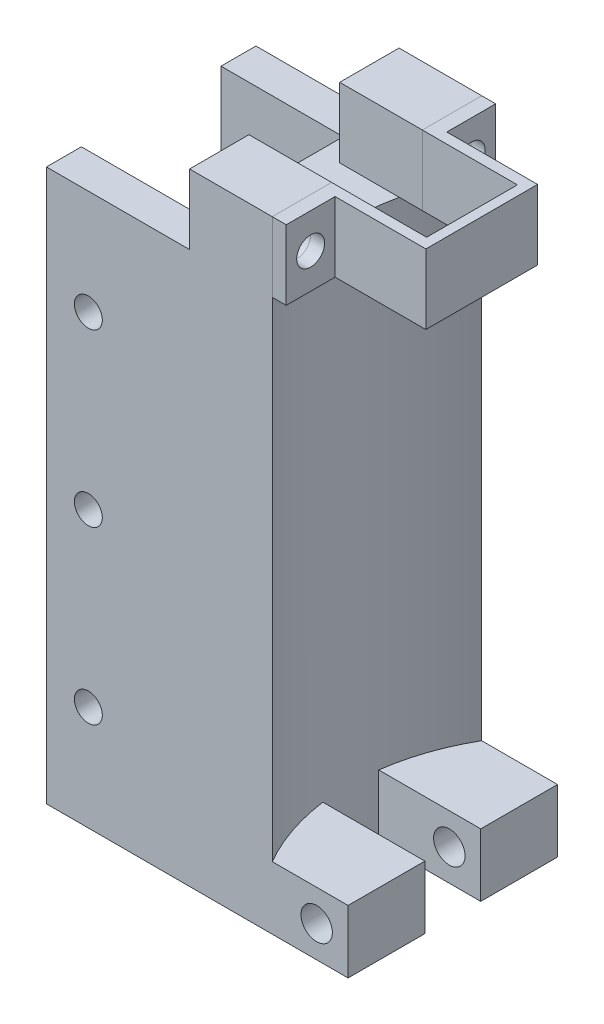
SolidWorks part; units mm, degrees
ref_plane "Front Plane" through (0, 0, 0) normal (0, 0, 1) x (1, 0, 0)
ref_plane "Top Plane" through (0, 0, 0) normal (0, 1, 0) x (1, 0, 0)
ref_plane "Right Plane" through (0, 0, 0) normal (1, 0, 0) x (0, 0, -1)
sketch "Sketch1" plane through (0, 0, 0) normal (0, 0, 1) x (1, 0, 0)
  line L1 (-7.5, -39.5) -> (7.5, -39.5)
  line L2 (-7.5, -39.5) -> (-7.5, 39.5)
  line L3 (-7.5, 39.5) -> (7.5, 39.5)
  line L4 (7.5, -39.5) -> (7.5, 39.5)
  line L5 (-7.5, -39.5) -> (7.5, 39.5) construction
  line L6 (-7.5, 39.5) -> (7.5, -39.5) construction
  point P0 (0, 0)
  dimension "D1" = 15
  dimension "D2" = 79
extrude "Boss-Extrude1" add sketch "Sketch1" along normal mid plane 30
sketch "Sketch2" plane through (0, 39.5, 0) normal (0, 1, 0) x (1, 0, 0)
  arc A0 (7.5, -15) -> (7.5, 15) centre (33.4808, 0) cw
  line M5 (7.5, -15) -> (7.5, 15)
  dimension "D1" = 30
extrude "Cut-Extrude1" cut sketch "Sketch2" against normal blind 70 and the other way through all contours A0 M5
sketch "Sketch3" plane through (7.5, 0, 0) normal (1, 0, 0) x (0, 0, -1)
  line L4 (15, -30.5) -> (-15, -30.5)
  line L5 (-15, -30.5) -> (-15, -39.5)
  line L6 (-15, -39.5) -> (15, -39.5)
  line L7 (15, -39.5) -> (15, -30.5)
  line L8 (15, -30.5) -> (-15, -30.5)
  line L9 (-15, -30.5) -> (-15, -39.5)
  line L10 (-15, -39.5) -> (15, -39.5)
  line L11 (15, -39.5) -> (15, -30.5)
  dimension "D1" = 0
extrude "Boss-Extrude2" add sketch "Sketch3" along normal blind 10.86
sketch "Sketch4" plane through (0, 0, -15) normal (0, 0, -1) x (-1, 0, 0)
  line L6 (-7.5, 39.5) -> (-7.5, -30.5)
  line L7 (-7.5, -30.5) -> (-18.36, -30.5)
  line L8 (-18.36, -30.5) -> (-18.36, -39.5)
  line L9 (-18.36, -39.5) -> (7.5, -39.5)
  line L10 (7.5, -39.5) -> (7.5, 39.5)
  line L11 (7.5, 39.5) -> (-7.5, 39.5)
  line L12 (-7.5, 39.5) -> (-7.5, -30.5)
  line L13 (-7.5, -30.5) -> (-18.36, -30.5)
  line L14 (-18.36, -30.5) -> (-18.36, -39.5)
  line L15 (-18.36, -39.5) -> (7.5, -39.5)
  line L16 (7.5, -39.5) -> (7.5, 39.5)
  line L17 (7.5, 39.5) -> (-7.5, 39.5)
  circle A0 centre (-13.86, -35) radius 2.25
  dimension "D2" = 4.5
  dimension "D4" = 4.5
  dimension "D3" = 4.5
  dimension "D1" = 0
extrude "Cut-Extrude2" cut sketch "Sketch4" against normal blind 50.86 contours A0
sketch "Sketch5" plane through (18.36, 0, 0) normal (1, 0, 0) x (0, 0, -1)
  line L0 (-15, -39.5) -> (15, -39.5) construction
  line L1 (-4, -39.5) -> (4, -39.5)
  line L2 (-4, -39.5) -> (-4, -30.5)
  line L3 (-4, -30.5) -> (4, -30.5)
  line L4 (4, -39.5) -> (4, -30.5)
  line L5 (15, -30.5) -> (-15, -30.5) construction
  line L6 (-15, -30.5) -> (-15, -39.5) construction
  line M6 (15, -30.5) -> (-15, -30.5)
  line M8 (-15, -39.5) -> (15, -39.5)
  dimension "D1" = 8
  dimension "D2" = 11
extrude "Cut-Extrude3" cut sketch "Sketch5" against normal up to surface (14.6114 mm away) contours L4 L2 M8 M6
sketch "Sketch8" plane through (0, 0, 0) normal (0, 0, 1) x (1, 0, 0)
  line L1 (0, -39.5) -> (-24.84, -39.5)
  line L2 (0, -39.5) -> (0, 39.5)
  line L3 (0, 39.5) -> (-24.84, 39.5)
  line L4 (-24.84, -39.5) -> (-24.84, 39.5)
  line L6 (-7.5, -39.5) -> (18.36, -39.5)
  line L7 (18.36, -39.5) -> (18.36, -30.5)
  line L8 (18.36, -30.5) -> (7.5, -30.5)
  line L9 (7.5, -30.5) -> (7.5, 39.5)
  line L10 (7.5, 39.5) -> (-7.5, 39.5)
  line L11 (-7.5, 39.5) -> (-7.5, -39.5)
  line L12 (-7.5, -39.5) -> (18.36, -39.5)
  line L13 (18.36, -39.5) -> (18.36, -30.5)
  line L14 (18.36, -30.5) -> (7.5, -30.5)
  line L15 (7.5, -30.5) -> (7.5, 39.5)
  line L16 (7.5, 39.5) -> (-7.5, 39.5)
  line L17 (-7.5, 39.5) -> (-7.5, -39.5)
  dimension "D2" = 24.84
  dimension "D1" = 0
extrude "Boss-Extrude3" add sketch "Sketch8" along normal mid plane 30 contours L17 L3 L4 L1
sketch "Sketch9" plane through (-24.84, 0, 0) normal (-1, 0, 0) x (0, 0, 1)
  line L0 (15, -39.5) -> (-15, -39.5) construction
  line L1 (-10, -39.5) -> (10, -39.5)
  line L2 (-10, -39.5) -> (-10, 39.5)
  line L3 (-10, 39.5) -> (10, 39.5)
  line L4 (10, -39.5) -> (10, 39.5)
  line L5 (15, 39.5) -> (-15, 39.5) construction
  point P8 (0, 39.5)
  dimension "D1" = 20
extrude "Cut-Extrude4" cut sketch "Sketch9" against normal mid plane 35
sketch "Sketch10" plane through (0, 0, 15) normal (0, 0, 1) x (1, 0, 0)
  line L0 (-18.84, 39.5) -> (-18.84, -39.5) construction
  line L1 (-24.84, -39.5) -> (-12.84, -39.5)
  line L2 (-24.84, -39.5) -> (-24.84, 39.5)
  line L3 (-24.84, 39.5) -> (-12.84, 39.5)
  line L4 (-12.84, -39.5) -> (-12.84, 39.5)
  line L6 (-24.84, -39.5) -> (18.36, -39.5)
  line L7 (18.36, -39.5) -> (18.36, -30.5)
  line L8 (18.36, -30.5) -> (7.5, -30.5)
  line L9 (7.5, -30.5) -> (7.5, 39.5)
  line L10 (7.5, 39.5) -> (-24.84, 39.5)
  line L11 (-24.84, 39.5) -> (-24.84, -39.5)
  line L12 (-24.84, -39.5) -> (18.36, -39.5)
  line L13 (18.36, -39.5) -> (18.36, -30.5)
  line L14 (18.36, -30.5) -> (7.5, -30.5)
  line L15 (7.5, -30.5) -> (7.5, 39.5)
  line L16 (7.5, 39.5) -> (-24.84, 39.5)
  line L17 (-24.84, 39.5) -> (-24.84, -39.5)
  circle A0 centre (-18.84, 24.5) radius 2
  circle A1 centre (-18.84, 0) radius 2
  circle A2 centre (-18.84, -24.5) radius 2
  dimension "D3" = 4
  dimension "D4" = 15
  dimension "D5" = 15
  dimension "D2" = 12
  dimension "D1" = 0
extrude "Cut-Extrude5" cut sketch "Sketch10" against normal mid plane 80 contours L0 A0 | A0 L0 | A2 | A1
sketch "Sketch11" plane through (0, 39.5, 0) normal (0, 1, 0) x (1, 0, 0)
  line L0 (-7.34, -10) -> (7.5, -10)
  line L1 (7.5, -15) -> (-7.34, -15)
  line L2 (7.5, -15) -> (7.5, 15)
  line L3 (7.5, 15) -> (-7.34, 15)
  line L4 (-7.34, -15) -> (-7.34, 15)
  line L5 (-7.34, 10) -> (7.5, 10)
  line L7 (-24.84, 15) -> (-24.84, 10)
  line L8 (-24.84, 10) -> (-7.34, 10)
  line L9 (-7.34, 10) -> (-7.34, -10)
  line L10 (-7.34, -10) -> (-24.84, -10)
  line L11 (-24.84, -10) -> (-24.84, -15)
  line L12 (-24.84, -15) -> (7.5, -15)
  line L13 (7.5, 15) -> (-24.84, 15)
  line L14 (-24.84, 15) -> (-24.84, 10)
  line L15 (-24.84, 10) -> (-7.34, 10)
  line L16 (-7.34, 10) -> (-7.34, -10)
  line L17 (-7.34, -10) -> (-24.84, -10)
  line L18 (-24.84, -10) -> (-24.84, -15)
  line L19 (-24.84, -15) -> (7.5, -15)
  line L20 (7.5, 15) -> (-24.84, 15)
  line L23 (-7.34, -6.5) -> (7.5, -6.5)
  line L24 (-1000, 0) -> (49000, 0) construction
  line L25 (-7.34, 6.5) -> (7.5, 6.5)
  line L26 (-4.34, 15) -> (-4.34, -15)
  arc A1 (7.5, 15) -> (7.5, -15) centre (33.4808, 0) ccw
  arc A2 (7.5, 15) -> (7.5, -15) centre (33.4808, 0) ccw
  line M12 (-7.34, 10) -> (-7.34, -10)
  line M15 (-24.84, -15) -> (7.5, -15)
  arc M16 (7.5, -15) -> (7.5, 15) centre (33.4808, 0) cw
  line M17 (7.5, 15) -> (-24.84, 15)
  dimension "D2" = 8.5
  dimension "D3" = 3
  dimension "D1" = 0
extrude "Boss-Extrude4" add sketch "Sketch11" along normal blind 10 contours L4 L0 M15 M16 | L23 L16 L0 M16 | L23 L0 L2 M16 | L2 L0 M16 | L4 L5 M16 M17 | L25 L5 M12 M16 | L5 L2 M16 | L25 L2 L5 M16
sketch "Sketch12" plane through (7.5, 0, 0) normal (1, 0, 0) x (0, 0, -1)
  line L0 (0, -1000) -> (0, 49000) construction
  line L1 (6.5, 39.5) -> (15, 39.5) construction
  line L2 (15, 49.5) -> (15, 39.5) construction
  line L4 (15, 39.5) -> (15, 49.5) construction
  line L5 (15, 49.5) -> (6.5, 49.5) construction
  line L6 (6.5, 49.5) -> (6.5, 39.5) construction
  line L7 (-15, 39.5) -> (-6.5, 39.5) construction
  line L8 (-6.5, 39.5) -> (-6.5, 49.5) construction
  line L9 (-6.5, 49.5) -> (-15, 49.5) construction
  line L10 (-15, 49.5) -> (-15, 39.5) construction
  line L11 (6.5, 39.5) -> (15, 39.5)
  line L12 (15, 39.5) -> (15, 49.5)
  line L13 (15, 49.5) -> (6.5, 49.5)
  line L14 (6.5, 49.5) -> (6.5, 39.5)
  line L15 (-15, 39.5) -> (-6.5, 39.5)
  line L16 (-6.5, 39.5) -> (-6.5, 49.5)
  line L17 (-6.5, 49.5) -> (-15, 49.5)
  line L18 (-15, 49.5) -> (-15, 39.5)
  circle A0 centre (11.25, 44.5) radius 1.5
  circle A1 centre (-11.25, 44.5) radius 1.5
  dimension "D1" = 3
  dimension "D2" = 5
  dimension "D3" = 3.75
extrude "Cut-Extrude6" cut sketch "Sketch12" against normal mid plane 30 contours A1 | A0
sketch "Sketch13" plane through (0, 49.5, 0) normal (0, 1, 0) x (1, 0, 0)
  line L1 (7.5, 15) -> (-4.34, 15) construction
  line L2 (-4.34, 15) -> (-4.34, 6.5) construction
  line L3 (-4.34, 6.5) -> (7.5, 6.5) construction
  line L4 (7.5, 6.5) -> (7.5, 15) construction
  line L5 (7.5, -15) -> (7.5, -6.5) construction
  line L6 (7.5, -6.5) -> (-4.34, -6.5) construction
  line L7 (-4.34, -6.5) -> (-4.34, -15) construction
  line L8 (-4.34, -15) -> (7.5, -15) construction
  line L9 (7.5, 15) -> (-4.34, 15)
  line L10 (-4.34, 15) -> (-4.34, 6.5)
  line L11 (-4.34, 6.5) -> (7.5, 6.5)
  line L12 (7.5, 6.5) -> (7.5, 15)
  line L13 (7.5, -15) -> (7.5, -6.5)
  line L14 (7.5, -6.5) -> (-4.34, -6.5)
  line L15 (-4.34, -6.5) -> (-4.34, -15)
  line L16 (-4.34, -15) -> (7.5, -15)
sketch "Sketch14" plane through (7.5, 0, 0) normal (1, 0, 0) x (0, 0, -1)
  line L1 (-15, 39.5) -> (15, 39.5)
  line L2 (-15, 39.5) -> (-15, 49.5)
  line L3 (-15, 49.5) -> (15, 49.5)
  line L4 (15, 39.5) -> (15, 49.5)
extrude "Boss-Extrude5" add sketch "Sketch14" along normal blind 15
sketch "Sketch15" plane through (0, 49.5, 0) normal (0, 1, 0) x (1, 0, 0)
  line L0 (8.75, -15) -> (8.75, -6.5)
  line L1 (8.75, -6.5) -> (21.11, -6.5)
  line L2 (21.11, -6.5) -> (21.11, 6.5)
  line L3 (21.11, 6.5) -> (8.75, 6.5)
  line L4 (8.75, 6.5) -> (8.75, 15)
  line L5 (9.5, 15) -> (9.5, 8)
  line L6 (9.5, 8) -> (22.5, 8)
  line L7 (9.5, -15) -> (9.5, -8)
  line L8 (-4.34, -15) -> (22.5, -15)
  line L9 (22.5, -15) -> (22.5, 15)
  line L10 (22.5, 15) -> (-4.34, 15)
  line L11 (-4.34, 15) -> (-4.34, 6.5)
  line L12 (-4.34, 6.5) -> (7.5, 6.5)
  line L13 (7.5, 6.5) -> (7.5, -6.5)
  line L14 (7.5, -6.5) -> (-4.34, -6.5)
  line L15 (-4.34, -6.5) -> (-4.34, -15)
  line L16 (-4.34, -15) -> (22.5, -15)
  line L17 (22.5, -15) -> (22.5, 15)
  line L18 (22.5, 15) -> (-4.34, 15)
  line L19 (-4.34, 15) -> (-4.34, 6.5)
  line L20 (-4.34, 6.5) -> (7.5, 6.5)
  line L21 (7.5, 6.5) -> (7.5, -6.5)
  line L22 (7.5, -6.5) -> (-4.34, -6.5)
  line L23 (-4.34, -6.5) -> (-4.34, -15)
  line L24 (9.5, -8) -> (22.5, -8)
  line L25 (8.75, 6.5) -> (7.5, 6.5)
  line L26 (8.75, -6.5) -> (7.5, -6.5)
  line M10 (-4.34, -15) -> (22.5, -15)
  line M11 (22.5, -15) -> (22.5, 15)
  line M12 (22.5, 15) -> (-4.34, 15)
  line M15 (7.5, 6.5) -> (7.5, -6.5)
  dimension "D2" = 12.36
  dimension "D3" = 1.25
  dimension "D4" = 7
  dimension "D5" = 13
  dimension "D1" = 0
extrude "Cut-Extrude7" cut sketch "Sketch15" against normal blind 13 contours L24 L7 M10 M11 | L5 L6 M11 M12 | L26 L1 L2 L3 L25 M15
sketch "Sketch17" plane through (0, 0, 15) normal (0, 0, 1) x (1, 0, 0)
  line L0 (7.5, 39.5) -> (7.5, 49.5)
  line L1 (-4.34, 49.5) -> (7.5, 49.5) construction
  line L2 (-4.34, 49.5) -> (9.5, 49.5) construction
split "Split1" trim tools "Sketch17" bodies to split 115 resulting bodies 116 117
sketch "Sketch18" plane through (22.5, 0, 0) normal (1, 0, 0) x (0, 0, -1)
  line L0 (15, 39.5) -> (15, 49.5) construction
  line L1 (15, 49.5) -> (8, 49.5) construction
  line L2 (8, 49.5) -> (8, 39.5) construction
  line L3 (8, 39.5) -> (15, 39.5) construction
  line L4 (-15, 39.5) -> (-8, 39.5) construction
  line L5 (-8, 39.5) -> (-8, 49.5) construction
  line L6 (-8, 49.5) -> (-15, 49.5) construction
  line L7 (-15, 49.5) -> (-15, 39.5) construction
  line L8 (15, 39.5) -> (15, 49.5)
  line L9 (15, 49.5) -> (8, 49.5)
  line L10 (8, 49.5) -> (8, 39.5)
  line L11 (8, 39.5) -> (15, 39.5)
  line L12 (-15, 39.5) -> (-8, 39.5)
  line L13 (-8, 39.5) -> (-8, 49.5)
  line L14 (-8, 49.5) -> (-15, 49.5)
  line L15 (-15, 49.5) -> (-15, 39.5)
  line L16 (0, -1000) -> (0, 49000) construction
  circle A0 centre (11.5, 44.5) radius 2
  circle A1 centre (-11.5, 44.5) radius 2
  point P12 (11.5, 49.5)
  point P15 (15, 44.5)
  dimension "D1" = 4
extrude "Cut-Extrude8" cut sketch "Sketch18" against normal blind 43 contours A1 | A0
